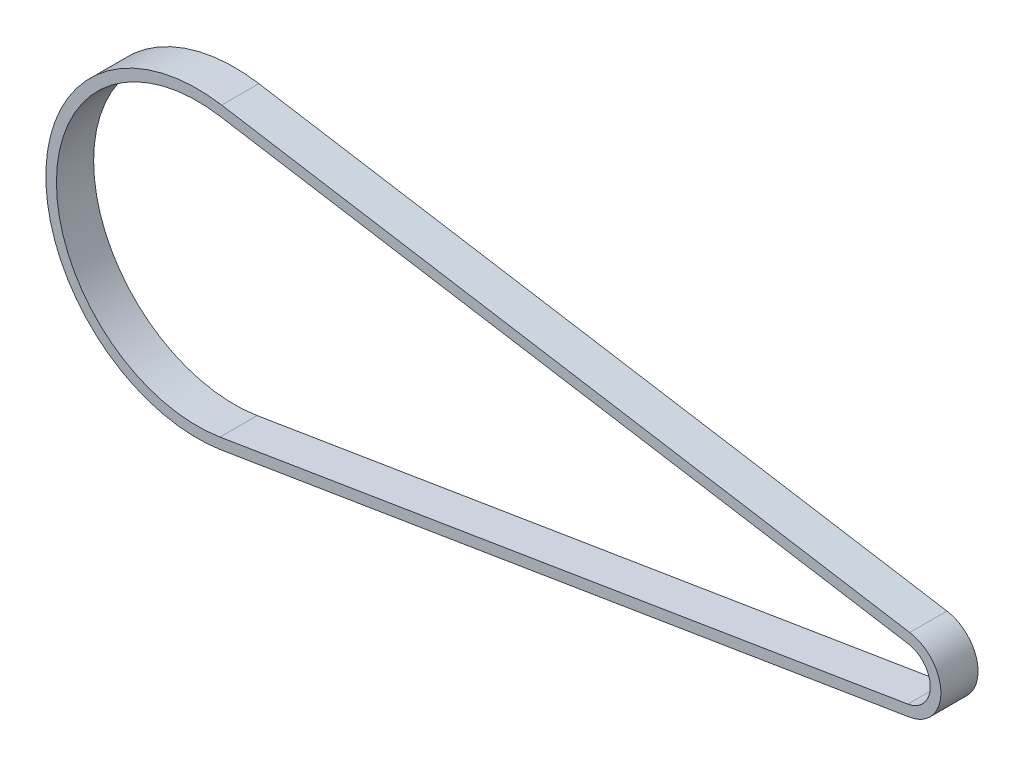
SolidWorks part; units mm, degrees
ref_plane "Front Plane" through (0, 0, 0) normal (0, 0, 1) x (1, 0, 0)
ref_plane "Top Plane" through (0, 0, 0) normal (0, 1, 0) x (1, 0, 0)
ref_plane "Right Plane" through (0, 0, 0) normal (1, 0, 0) x (0, 0, -1)
sketch "Sketch1" plane through (0, 0, 0) normal (0, 0, 1) x (1, 0, 0)
  line L0 (0, 0) -> (26.5, 0) construction
  line L1 (4.2838, 26.1515) -> (133.8083, 4.9342)
  line L2 (4.2838, -26.1515) -> (133.8083, -4.9342)
  line L3 (4.6071, 28.1252) -> (134.1316, 6.9079)
  line L4 (4.6071, -28.1252) -> (134.1316, -6.9079)
  arc A0 (4.2838, 26.1515) -> (4.2838, -26.1515) centre (0, 0) ccw
  arc A1 (133.8083, -4.9342) -> (133.8083, 4.9342) centre (133, 0) ccw
  arc A2 (134.1316, -6.9079) -> (134.1316, 6.9079) centre (133, 0) ccw
  arc A3 (4.6071, 28.1252) -> (4.6071, -28.1252) centre (0, 0) ccw
  dimension "D1" = 10
  dimension "D2" = 53
  dimension "D3" = 133
  dimension "D4" = 2
extrude "Boss-Extrude1" add sketch "Sketch1" along normal blind 7
